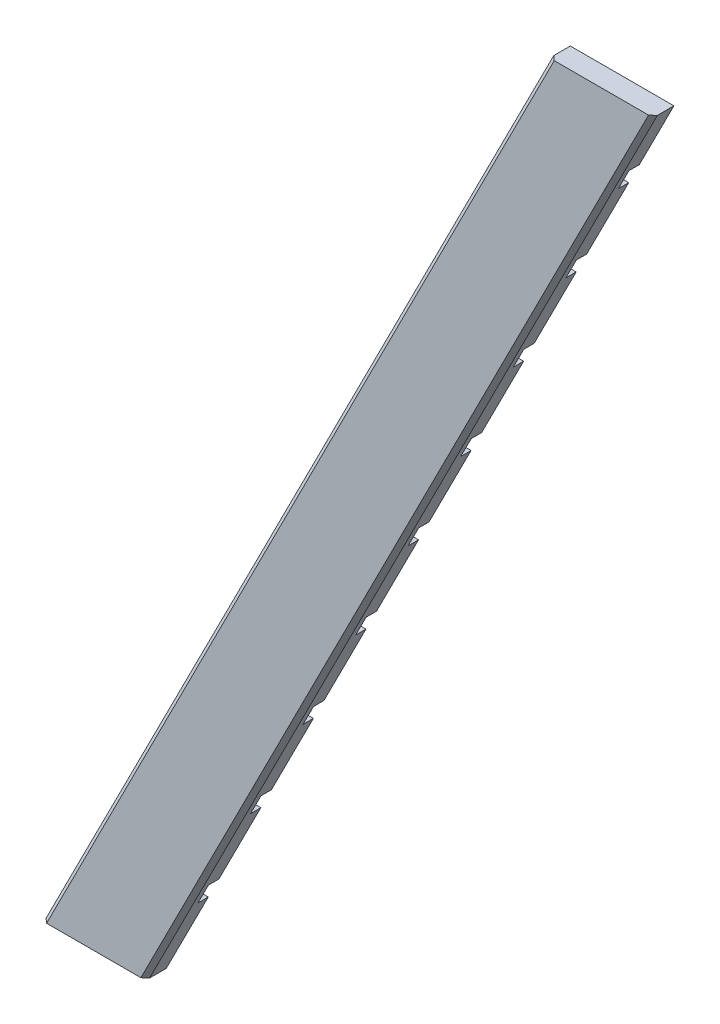
SolidWorks part; units mm, degrees
ref_plane "Спереди" through (0, 0, 0) normal (0, 0, 1) x (1, 0, 0)
ref_plane "Сверху" through (0, 0, 0) normal (0, 1, 0) x (1, 0, 0)
ref_plane "Справа" through (0, 0, 0) normal (1, 0, 0) x (0, 0, -1)
sketch "Эскиз1" plane through (0, 0, 0) normal (0, 0, 1) x (1, 0, 0)
  line L0 (0, 0) -> (24.5, 48.3)
  line L1 (24.5, 48.3) -> (19.5, 48.3)
  line L2 (19.5, 48.3) -> (-5, 0)
  line L3 (-5, 0) -> (0, 0)
  dimension "D1" = 24.5
  dimension "D2" = 48.3
  dimension "D3" = 5
extrude "Бобышка-Вытянуть1" add sketch "Эскиз1" along normal blind 1
sketch "Эскиз2" plane through (0, 0, 1) normal (0, 0, 1) x (1, 0, 0)
  line L0 (-5, 0) -> (0, 0) construction
  line L1 (30.3187, 4) -> (-4.1285, 4)
  line L2 (30.3187, 4) -> (30.3187, 5)
  line L3 (30.3187, 5) -> (-4.1285, 5)
  line L4 (-4.1285, 4) -> (-4.1285, 5)
  line L5 (30.3187, 4) -> (-4.1285, 5) construction
  line L6 (30.3187, 5) -> (-4.1285, 4) construction
  line L7 (30.3187, 10) -> (-4.1285, 10)
  line L8 (30.3187, 9) -> (-4.1285, 9)
  line L9 (30.3187, 9) -> (30.3187, 10)
  line L10 (-4.1285, 9) -> (-4.1285, 10)
  line L11 (30.3187, 15) -> (-4.1285, 15)
  line L12 (30.3187, 14) -> (-4.1285, 14)
  line L13 (30.3187, 14) -> (30.3187, 15)
  line L14 (-4.1285, 14) -> (-4.1285, 15)
  line L15 (30.3187, 20) -> (-4.1285, 20)
  line L16 (30.3187, 19) -> (-4.1285, 19)
  line L17 (30.3187, 19) -> (30.3187, 20)
  line L18 (-4.1285, 19) -> (-4.1285, 20)
  line L19 (30.3187, 25) -> (-4.1285, 25)
  line L20 (30.3187, 24) -> (-4.1285, 24)
  line L21 (30.3187, 24) -> (30.3187, 25)
  line L22 (-4.1285, 24) -> (-4.1285, 25)
  line L23 (30.3187, 30) -> (-4.1285, 30)
  line L24 (30.3187, 29) -> (-4.1285, 29)
  line L25 (30.3187, 29) -> (30.3187, 30)
  line L26 (-4.1285, 29) -> (-4.1285, 30)
  line L27 (30.3187, 35) -> (-4.1285, 35)
  line L28 (30.3187, 34) -> (-4.1285, 34)
  line L29 (30.3187, 34) -> (30.3187, 35)
  line L30 (-4.1285, 34) -> (-4.1285, 35)
  line L31 (30.3187, 40) -> (-4.1285, 40)
  line L32 (30.3187, 39) -> (-4.1285, 39)
  line L33 (30.3187, 39) -> (30.3187, 40)
  line L34 (-4.1285, 39) -> (-4.1285, 40)
  line L35 (30.3187, 45) -> (-4.1285, 45)
  line L36 (30.3187, 44) -> (-4.1285, 44)
  line L37 (30.3187, 44) -> (30.3187, 45)
  line L38 (-4.1285, 44) -> (-4.1285, 45)
  point P0 (13.0951, 4.5)
  dimension "D1" = 1
  dimension "D2" = 4
  dimension "D3" = 9
extrude "Вырез-Вытянуть1" cut sketch "Эскиз2" against normal blind 0.5
mirror "Зеркальное отражение1" about plane through (0, 0, 1) normal (0, 0, 1) of bodies 104
delete or keep bodies "Тело-Удалить/Сохранить 1" type delete bodies bodies 104
chamfer "Фаска1" distance 0.2 angle 45 2 edges at (12.25, 24.15, 2) (7.25, 24.15, 2)
